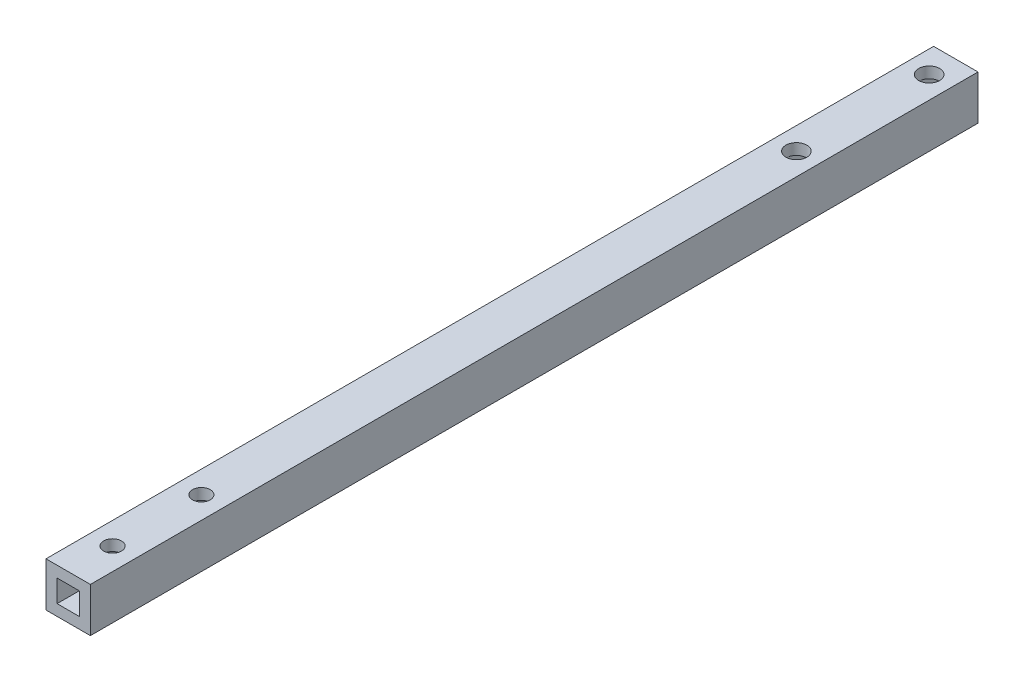
SolidWorks part; units mm, degrees
material "6061 Alloy"
ref_plane "Front Plane" through (0, 0, 0) normal (0, 0, 1) x (1, 0, 0)
ref_plane "Top Plane" through (0, 0, 0) normal (0, 1, 0) x (1, 0, 0)
ref_plane "Right Plane" through (0, 0, 0) normal (1, 0, 0) x (0, 0, -1)
sketch "Sketch1" plane through (0, 0, 0) normal (0, 0, 1) x (1, 0, 0)
  line L1 (-3.175, -3.175) -> (3.175, -3.175)
  line L2 (-3.175, -3.175) -> (-3.175, 3.175)
  line L3 (-3.175, 3.175) -> (3.175, 3.175)
  line L4 (3.175, -3.175) -> (3.175, 3.175)
  line L5 (-3.175, -3.175) -> (3.175, 3.175) construction
  line L6 (-3.175, 3.175) -> (3.175, -3.175) construction
  line L7 (-1.5875, -1.5875) -> (1.5875, -1.5875)
  line L8 (-1.5875, -1.5875) -> (-1.5875, 1.5875)
  line L9 (-1.5875, 1.5875) -> (1.5875, 1.5875)
  line L10 (1.5875, -1.5875) -> (1.5875, 1.5875)
  line L11 (-1.5875, -1.5875) -> (1.5875, 1.5875) construction
  line L12 (-1.5875, 1.5875) -> (1.5875, -1.5875) construction
  point P0 (0, 0)
  point P6 (0, 0)
  dimension "D1" = 6.35
  dimension "D2" = 6.35
  dimension "D3" = 1.5875
  dimension "D4" = 1.5875
extrude "Boss-Extrude1" add sketch "Sketch1" along normal blind 127
sketch "Sketch3" plane through (0, 3.175, 0) normal (0, 1, 0) x (1, 0, 0)
  line L1 (0, 0) -> (0, -205.0928) construction
  line L2 (3.175, -127) -> (-3.175, -127) construction
  circle A0 centre (0, -120.65) radius 1.27
  circle A1 centre (0, -107.95) radius 1.27
  dimension "D1" = 2.54
  dimension "D2" = 6.35
  dimension "D3" = 2.54
  dimension "D4" = 12.7
extrude "Cut-Extrude1" cut sketch "Sketch3" against normal blind 12.7
sketch "Sketch4" plane through (0, 3.175, 0) normal (0, 1, 0) x (1, 0, 0)
  line L0 (0, 0) -> (0, -134.0259) construction
  line L1 (3.175, 0) -> (-3.175, 0) construction
  line L2 (-6.8945, -13.31) -> (15.4744, -13.31) construction
  circle A0 centre (0, -3.81) radius 1.5
  circle A1 centre (0, -22.81) radius 1.5
  point P3 (0, -13.31)
  point P4 (0, -3.81)
  dimension "D3" = 3
  dimension "D1" = 9.5
  dimension "D2" = 3.81
extrude "Cut-Extrude2" cut sketch "Sketch4" against normal blind 12.7
